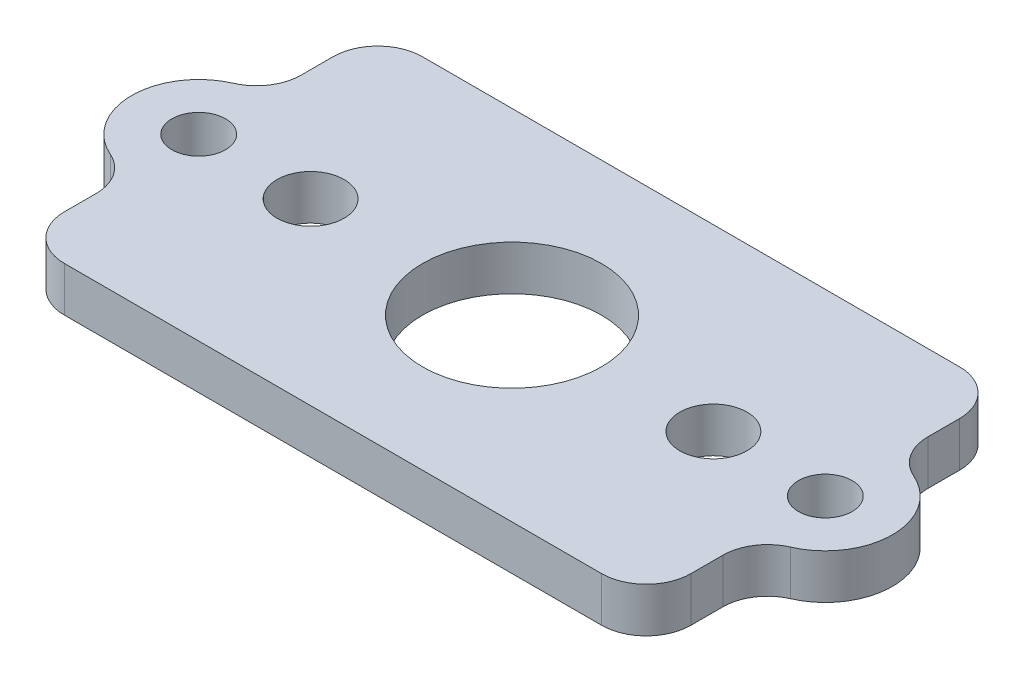
SolidWorks part; units mm, degrees
ref_plane "Спереди" through (0, 0, 0) normal (0, 0, 1) x (1, 0, 0)
ref_plane "Сверху" through (0, 0, 0) normal (0, 1, 0) x (1, 0, 0)
ref_plane "Справа" through (0, 0, 0) normal (1, 0, 0) x (0, 0, -1)
sketch "Sketch1" plane through (0, 0, 0) normal (0, 0, 1) x (1, 0, 0)
  line L0 (0, 0) -> (-7, 0)
  line L1 (-7, 0) -> (-7, 8)
  line L2 (-7, 8) -> (7, 8)
  line L3 (7, 8) -> (7, 0)
  line L4 (7, 0) -> (0, 0)
extrude "Extrude1" add sketch "Sketch1" along normal mid plane 8
sketch "Sketch2" plane through (0, 0, 0) normal (0, 0, 1) x (1, 0, 0)
  line L0 (7, 8) -> (7, 5.5) construction
  line L1 (7, 5.5) -> (4.5, 5.5) construction
  circle A0 centre (4.5, 5.5) radius 1
extrude "Extrude2" cut sketch "Sketch2" against normal through all both and the other way through all
sketch "Sketch3" plane through (0, 0, 0) normal (0, 0, 1) x (1, 0, 0)
  line L0 (-7, 8) -> (-3, 8)
  line L1 (-3, 8) -> (-3, 4.5)
  circle A0 centre (-3, 4.5) radius 1.5
sketch "Sketch4" plane through (0, 0, 0) normal (1, 0, 0) x (0, 0, -1)
  line L0 (0, 0) -> (0, 1)
  line L1 (3, 1) -> (-3, 1)
  line L2 (-3, 1) -> (-3, 9.732)
  line L3 (3, 1) -> (3, 9.732)
  line L4 (-3, 9.732) -> (3, 9.732)
extrude "Extrude3" cut sketch "Sketch4" against normal through all both and the other way through all contours L4 L2 L1 L3
fillet "Fillet2" radius 1 4 edges at (7, 8, -3.5) (7, 8, 3.5) (-7, 8, -3.5) (-7, 8, 3.5)
extrude "Extrude4" add sketch "Sketch3" along normal blind 14 and the other way blind 3
sketch "Sketch5" plane through (0, 0, 14) normal (0, 0, 1) x (1, 0, 0)
  line L0 (-1.5, 4.5) -> (-4, 4.5)
  line L1 (-4, 4.5) -> (-4, 6.0607)
  line L2 (-4, 6.0607) -> (-4.9564, 6.0607)
  line L3 (-4.9564, 6.0607) -> (-4.9564, 2.5)
  line L4 (-4.9564, 2.5) -> (-4, 2.5)
  line L5 (-4, 2.5) -> (-4, 4.5)
  circle A0 centre (-3, 4.5) radius 1.5 construction
  circle A1 centre (-3, 4.5) radius 1.5 construction
  circle M1 centre (-3, 4.5) radius 1.5
extrude "Extrude5" cut sketch "Sketch5" against normal blind 9 contours L4 L5 L1 L2 L3 M1 | L5 L1 M1
sketch "Sketch6" plane through (0, 0, 0) normal (0, -1, 0) x (1, 0, 0)
  line L0 (0, 0) -> (-8.5, 0)
  line L2 (0, 0) -> (0, 5.5899)
  circle A1 centre (-7, 0) radius 1.5
  circle A2 centre (0, 0) radius 6
  circle A3 centre (7, 0) radius 1.5
extrude "Extrude6" add sketch "Sketch6" against normal blind 1
sketch "Sketch7" plane through (0, 0, 0) normal (0, -1, 0) x (1, 0, 0)
  circle A0 centre (-7, 0) radius 0.6
  circle A1 centre (7, 0) radius 0.6
extrude "Extrude7" cut sketch "Sketch7" against normal blind 1
fillet "Fillet3" radius 1 4 edges at (7, 0.5, -1.5) (7, 0.5, 1.5) (-7, 0.5, 1.5) (-7, 0.5, -1.5)
sketch "Sketch8" plane through (0, 0, 0) normal (0, -1, 0) x (1, 0, 0)
  circle A0 centre (0, 0) radius 2
extrude "Extrude8" cut sketch "Sketch8" against normal blind 1
sketch "Sketch9" plane through (0, 1, 0) normal (0, 1, 0) x (1, 0, 0)
  circle A0 centre (0, 0) radius 15.1587
extrude "Extrude9" cut sketch "Sketch9" along normal through all
sketch "Эскиз2" plane through (0, 1, 0) normal (0, 1, 0) x (1, 0, 0)
  line L0 (0, 0) -> (0, 4.9503) construction
  line L2 (4.5, 0) -> (-4.5, 0)
  circle A0 centre (-4.5, 0) radius 0.75
  circle A1 centre (4.5, 0) radius 0.75
  point P8 (0, 0)
extrude "Вырез-Вытянуть1" cut sketch "Эскиз2" against normal through all
fillet "Скругление1" radius 1 4 edges at (7, 0.5, 4) (7, 0.5, -4) (-7, 0.5, 4) (-7, 0.5, -4)
